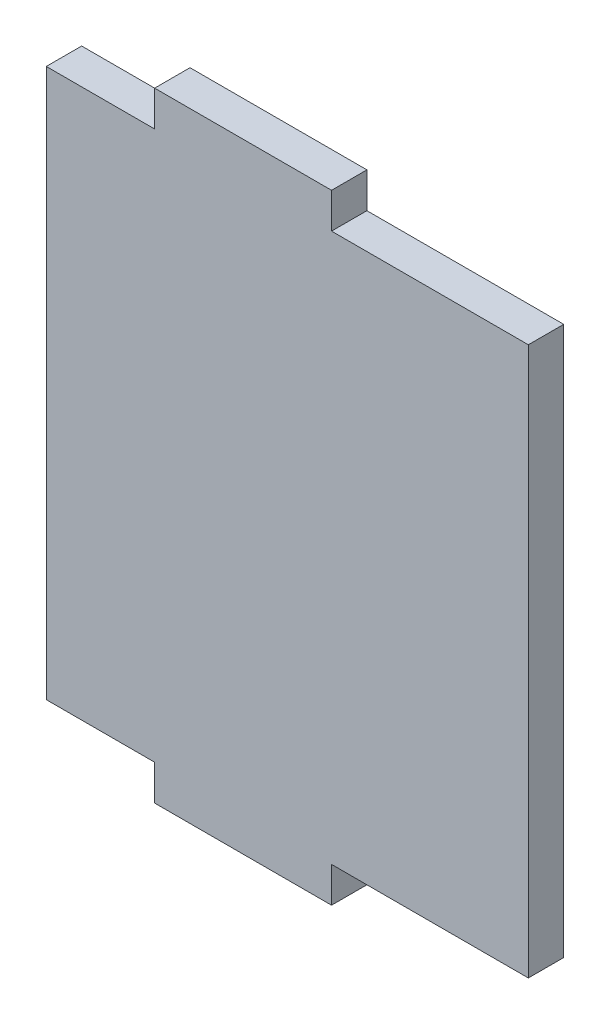
SolidWorks part; units mm, degrees
ref_plane "Front Plane" through (0, 0, 0) normal (0, 0, 1) x (1, 0, 0)
ref_plane "Top Plane" through (0, 0, 0) normal (0, 1, 0) x (1, 0, 0)
ref_plane "Right Plane" through (0, 0, 0) normal (1, 0, 0) x (0, 0, -1)
sketch "Sketch1" plane through (0, 0, 0) normal (0, 0, 1) x (1, 0, 0)
  line L0 (5, 31) -> (5, 35)
  line L1 (-27.25, 31) -> (-15, 31)
  line L2 (-27.25, 31) -> (-27.25, -31)
  line L3 (-27.25, -31) -> (-15, -31)
  line L4 (27.25, 31) -> (27.25, -31)
  line L5 (5, 35) -> (-15, 35)
  line L6 (-15, 35) -> (-15, 31)
  line L7 (5, 31) -> (27.25, 31)
  line L8 (0, 0) -> (33.5636, 0) construction
  line L9 (5, -31) -> (5, -35)
  line L11 (-15, -35) -> (-15, -31)
  line L12 (5, -31) -> (27.25, -31)
  line L13 (-27.25, -31) -> (-15, -31)
  line L14 (-27.25, 31) -> (-15, 31)
  line L15 (-15, -35) -> (5, -35)
  dimension "D1" = 54.5
  dimension "D2" = 62
  dimension "D3" = 4
  dimension "D4" = 27.25
  dimension "D5" = 20
  dimension "D6" = 22.25
  dimension "D7" = 4
extrude "Boss-Extrude1" add sketch "Sketch1" along normal blind 4
